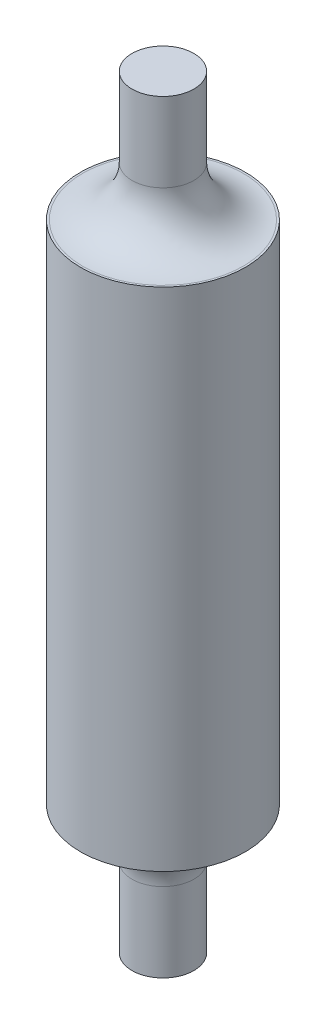
SolidWorks part; units mm, degrees
material "6061 Alloy"
ref_plane "Front Plane" through (0, 0, 0) normal (0, 0, 1) x (1, 0, 0)
ref_plane "Top Plane" through (0, 0, 0) normal (0, 1, 0) x (1, 0, 0)
ref_plane "Right Plane" through (0, 0, 0) normal (1, 0, 0) x (0, 0, -1)
sketch "Sketch1" plane through (0, 0, 0) normal (0, 1, 0) x (1, 0, 0)
  circle A0 centre (0, 0) radius 12.7
  dimension "D1" = 25.4
extrude "Boss-Extrude1" add sketch "Sketch1" along normal blind 77.978 contours A0
sketch "Sketch2" plane through (0, 77.978, 0) normal (0, 1, 0) x (1, 0, 0)
  circle A0 centre (0, 0) radius 4.7625
  dimension "D1" = 9.525
extrude "Boss-Extrude2" add sketch "Sketch2" along normal blind 19.812
ref_plane "Plane1" through (0, 38.989, 0) normal (0, 1, 0) x (1, 0, 0)
mirror "Mirror1" about plane through (0, 38.989, 0) normal (0, 1, 0) of "Boss-Extrude2"
fillet "Fillet1" radius 7.62 2 edges at (0, 77.978, 4.7625) (0, 0, 4.7625)
